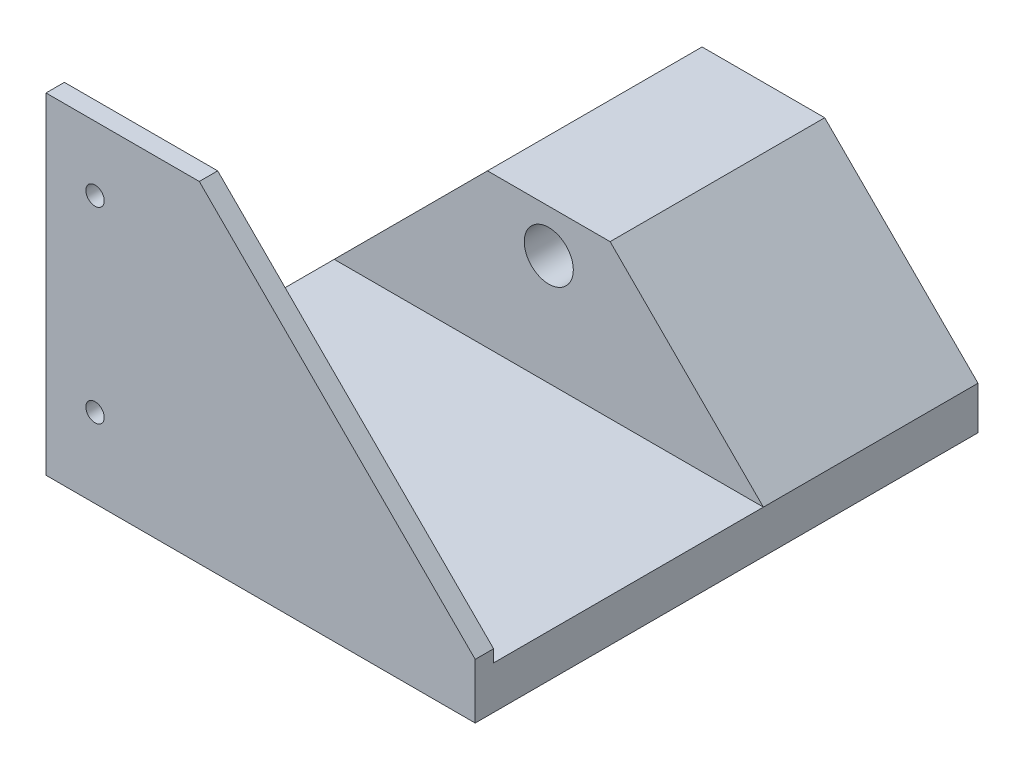
SolidWorks part; units mm, degrees
ref_plane "Front Plane" through (0, 0, 0) normal (0, 0, 1) x (1, 0, 0)
ref_plane "Top Plane" through (0, 0, 0) normal (0, 1, 0) x (1, 0, 0)
ref_plane "Right Plane" through (0, 0, 0) normal (1, 0, 0) x (0, 0, -1)
sketch "Sketch1" plane through (0, 0, 0) normal (0, 1, 0) x (1, 0, 0)
  line L1 (-35, -17.5) -> (35, -17.5)
  line L2 (-35, -17.5) -> (-35, 17.5)
  line L3 (-35, 17.5) -> (35, 17.5)
  line L4 (35, -17.5) -> (35, 17.5)
  line L5 (-35, -17.5) -> (35, 17.5) construction
  line L6 (-35, 17.5) -> (35, -17.5) construction
  point P0 (0, 0)
  dimension "D1" = 70
  dimension "D2" = 35
extrude "Boss-Extrude1" add sketch "Sketch1" along normal blind 32
sketch "Sketch2" plane through (0, 0, 17.5) normal (0, 0, 1) x (1, 0, 0)
  circle A0 centre (0, 25) radius 4
  dimension "D2" = 8
  dimension "D1" = 25
extrude "Cut-Extrude1" cut sketch "Sketch2" against normal blind 40
chamfer "Chamfer1" distance 25 angle 45 2 edges at (-35, 32, 0) (35, 32, 0)
sketch "Sketch3" plane through (0, 0, 17.5) normal (0, 0, 1) x (1, 0, 0)
  line L1 (-35, 7) -> (35, 7)
  line L2 (-35, 7) -> (-35, 0)
  line L3 (-35, 0) -> (35, 0)
  line L4 (35, 7) -> (35, 0)
extrude "Boss-Extrude2" add sketch "Sketch3" along normal blind 47
sketch "Sketch4" plane through (0, 7, 0) normal (0, 1, 0) x (1, 0, 0)
  line L0 (35, -64.5) -> (35, -17.5) construction
  line L1 (-35, -64.5) -> (35, -64.5)
  line L2 (-35, -64.5) -> (-35, -61.5)
  line L3 (-35, -61.5) -> (35, -61.5)
  line L4 (35, -64.5) -> (35, -61.5)
  dimension "D1" = 3
extrude "Boss-Extrude3" add sketch "Sketch4" along normal blind 47
sketch "Sketch5" plane through (0, 0, 61.5) normal (0, 0, -1) x (-1, 0, 0)
  line L0 (-35, 54) -> (-35, 7) construction
  line L1 (-35, 54) -> (35, 54) construction
  circle A0 centre (-18, 51) radius 1.5
  circle A1 centre (18, 51) radius 1.5
  dimension "D3" = 3
  dimension "D4" = 3
  dimension "D1" = 36
  dimension "D2" = 17
  dimension "D5" = 3
extrude "Cut-Extrude2" [suppressed] cut sketch "Sketch5" against normal blind 47
sketch "Sketch6" plane through (0, 0, 64.5) normal (0, 0, 1) x (1, 0, 0)
  line L1 (-35, 54) -> (-35, 0) construction
  line L2 (-35, 0) -> (35, 0) construction
  circle A0 centre (-27, 12.9) radius 1.5
  circle A1 centre (-27, 43.5) radius 1.5
  point P4 (0, 0)
  point P7 (-25.0426, 15.4)
  point P9 (-23.2725, 44.7754)
  dimension "D1" = 3
  dimension "D4" = 8
  dimension "D2" = 43.5
  dimension "D3" = 30.6
extrude "Cut-Extrude3" cut sketch "Sketch6" against normal blind 10
chamfer "Chamfer2" distance 45 angle 45 1 edges at (35, 54, 63)
